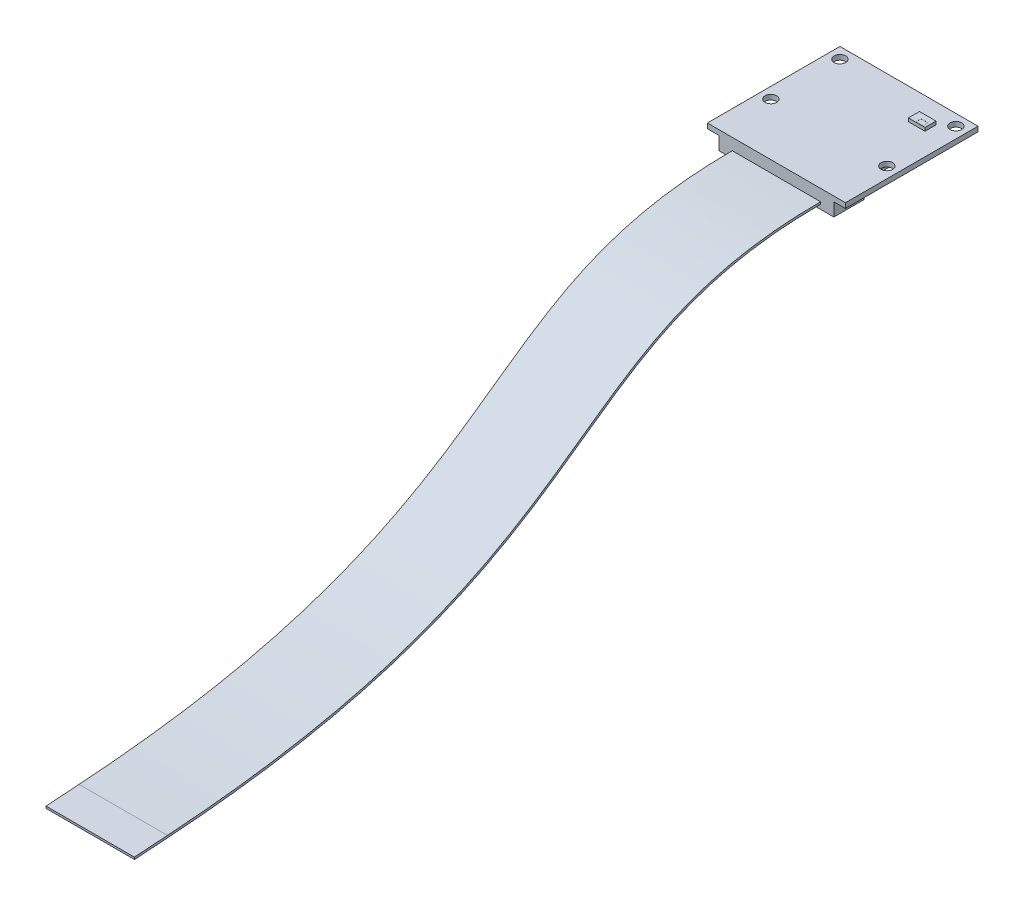
SolidWorks part; units mm, degrees
material "Epoxid, Ungefüllt"
ref_plane "Vorne" through (0, 0, 0) normal (0, 0, 1) x (1, 0, 0)
ref_plane "Oben" through (0, 0, 0) normal (0, 1, 0) x (1, 0, 0)
ref_plane "Rechts" through (0, 0, 0) normal (1, 0, 0) x (0, 0, -1)
sketch "Skizze1" plane through (0, 0, 0) normal (0, 1, 0) x (1, 0, 0)
  line L0 (0, 14.5) -> (0, -9.5) construction
  line L1 (-12.5, 14.5) -> (12.5, 14.5)
  line L2 (-12.5, 14.5) -> (-12.5, -9.5)
  line L3 (-12.5, -9.5) -> (12.5, -9.5)
  line L4 (12.5, 14.5) -> (12.5, -9.5)
  dimension "D1" = 24
  dimension "D2" = 25
  dimension "D3" = 9.5
extrude "PCB" add sketch "Skizze1" against normal blind 0.9
sketch "Skizze2" plane through (0, 0, 0) normal (0, 1, 0) x (1, 0, 0)
  line L0 (12.5, 14.5) -> (-12.5, 14.5) construction
  line L1 (12.5, -9.5) -> (12.5, 14.5) construction
  line L2 (0, 0) -> (0, 9.3158) construction
  circle A0 centre (10.5, 12.5) radius 1.05
  circle A1 centre (10.5, 0) radius 1.05
  circle A2 centre (-10.5, 0) radius 1.05
  circle A3 centre (-10.5, 12.5) radius 1.05
  dimension "D1" = 2.1
  dimension "D2" = 2
  dimension "D3" = 2
  dimension "D4" = 12.5
extrude "Mounting_Holes" cut sketch "Skizze2" against normal through all
sketch "Skizze3" plane through (0, -0.9, 0) normal (0, -1, 0) x (1, 0, 0)
  line L0 (0, 4) -> (0, 0) construction
  line L1 (-10.4, 9.5) -> (10.4, 9.5)
  line L2 (-10.4, 9.5) -> (-10.4, 4)
  line L3 (-10.4, 4) -> (10.4, 4)
  line L4 (10.4, 9.5) -> (10.4, 4)
  line L5 (-12.5, 9.5) -> (12.5, 9.5) construction
  dimension "D1" = 20.8
  dimension "D2" = 5.5
extrude "Connector_closed" add sketch "Skizze3" along normal blind 2.4
sketch "Skizze4" plane through (0, -0.9, 0) normal (0, -1, 0) x (1, 0, 0)
  line L0 (-12.5, -14.5) -> (-12.5, 9.5) construction
  line L1 (-9, -0.9) -> (8.7, -0.9)
  line L2 (-9, -0.9) -> (-9, -12.5)
  line L3 (-9, -12.5) -> (8.7, -12.5)
  line L4 (8.7, -0.9) -> (8.7, -12.5)
  line L5 (12.5, -14.5) -> (-12.5, -14.5) construction
  dimension "D1" = 17.7
  dimension "D2" = 3.5
  dimension "D3" = 2
  dimension "D4" = 13.6
extrude "Components_worst-case_Boundary-Box" add sketch "Skizze4" along normal blind 1.3
sketch "Skizze5" plane through (0, 0, 0) normal (1, 0, 0) x (0, 0, -1)
  line L0 (-9.5, -3.3) -> (-9.5, -0.9) construction
  line L1 (-9.5, 0) -> (14.5, 0) construction
  line L2 (-19.1541, -2.1) -> (0.1541, -2.1) construction
  line L3 (-127.75, -42.3233) -> (-133.7359, -42.7349)
  spline S0 degree 3 poles (-9.5, -2.1) (-57.963, -2.1) (-47.2649, -36.7884) (-127.75, -42.3233) knots 0 0 0 0 1 1 1 1
  point P1 (-107.2701, -11.7421)
  point P9 (-124.3331, -50.8053)
  point P11 (-127.75, -42.3233)
  dimension "D1" = 2.1
  dimension "D2" = 6
sketch "Skizze6" plane through (0, 0, 9.5) normal (0, 0, 1) x (1, 0, 0)
  line L1 (-8, -2.1) -> (8, -2.1)
  line L2 (-8, -2.1) -> (-8, -2.5)
  line L3 (-8, -2.5) -> (8, -2.5)
  line L4 (8, -2.1) -> (8, -2.5)
  dimension "D1" = 16
  dimension "D2" = 0.4
sweep "Cable_156mm_free_Length" add profiles "Skizze6" path "Skizze5"
sketch "Skizze7" plane through (0, 0, 0) normal (0, 1, 0) x (1, 0, 0)
  line L0 (12.5, 14.5) -> (-12.5, 14.5) construction
  line L1 (5.5, 10.9) -> (8.5, 10.9)
  line L2 (5.5, 10.9) -> (5.5, 8.9)
  line L3 (5.5, 8.9) -> (8.5, 8.9)
  line L4 (8.5, 10.9) -> (8.5, 8.9)
  line L5 (12.5, -9.5) -> (12.5, 14.5) construction
  dimension "D1" = 5.6
  dimension "D2" = 3.6
  dimension "D3" = 4
  dimension "D4" = 7
extrude "Components_worst-case_Boundary-Box2" add sketch "Skizze7" along normal blind 0.6
sketch "Skizze8" plane through (0, 0.6, 0) normal (0, 1, 0) x (1, 0, 0)
  line L0 (12.5, -9.5) -> (12.5, 14.5) construction
  line L1 (8.1, 9) -> (6.8, 9)
  line L2 (8.1, 9) -> (8.1, 9.9)
  line L3 (8.1, 9.9) -> (6.8, 9.9)
  line L4 (6.8, 9) -> (6.8, 9.9)
  line L5 (12.5, 14.5) -> (-12.5, 14.5) construction
  dimension "D1" = 1.3
  dimension "D2" = 0.9
  dimension "D3" = 4.4
  dimension "D4" = 4.6
extrude "Status_LED" cut sketch "Skizze8" against normal blind 0.01
